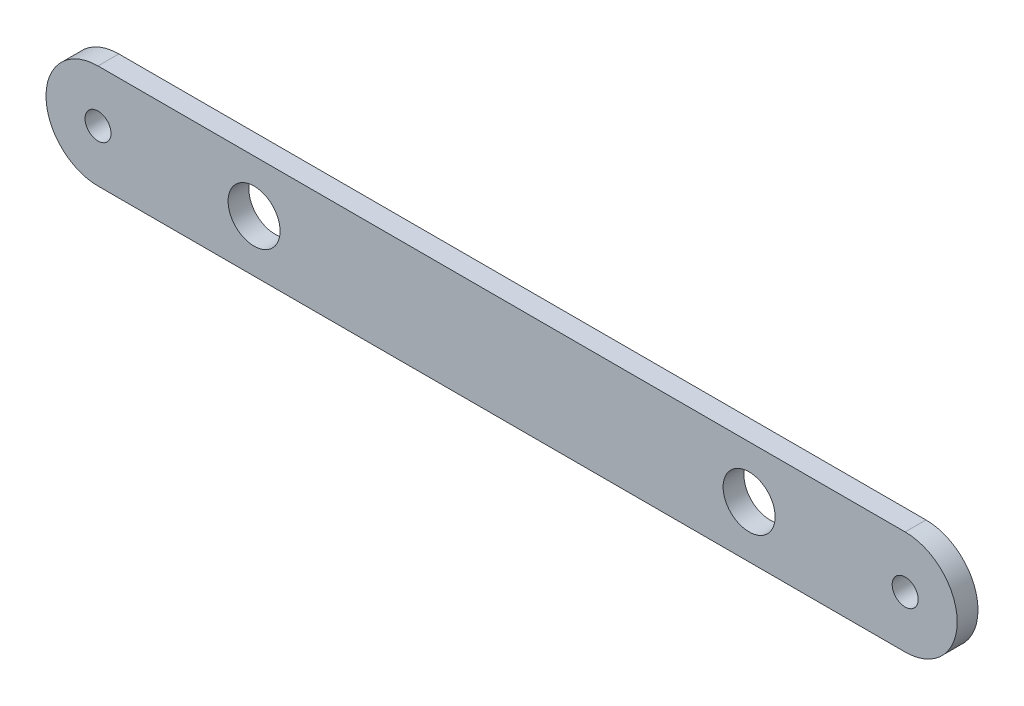
SolidWorks part; units mm, degrees
material "ABS"
ref_plane "Front Plane" through (0, 0, 0) normal (0, 0, 1) x (1, 0, 0)
ref_plane "Top Plane" through (0, 0, 0) normal (0, 1, 0) x (1, 0, 0)
ref_plane "Right Plane" through (0, 0, 0) normal (1, 0, 0) x (0, 0, -1)
sketch "Sketch1" plane through (0, 0, 0) normal (0, 0, 1) x (1, 0, 0)
  line L0 (0, 6.35) -> (98.5266, 6.35)
  line L1 (0, -6.35) -> (98.5266, -6.35)
  circle A0 centre (0, 0) radius 1.5875
  circle A1 centre (0, 0) radius 6.35
  circle A2 centre (98.5266, 0) radius 1.5875
  circle A3 centre (98.5266, 0) radius 6.35
  circle A4 centre (19.05, 0) radius 3.175
  circle A5 centre (79.4766, 0) radius 3.175
  dimension "D1" = 98.5266
  dimension "D2" = 3.175
  dimension "D3" = 12.7
  dimension "D4" = 19.05
  dimension "D5" = 19.05
  dimension "D6" = 6.35
extrude "Boss-Extrude1" add sketch "Sketch1" along normal blind 2.54 contours A1 A0 | A3 L0 A1 L1 A5 A4 | A3 A2
